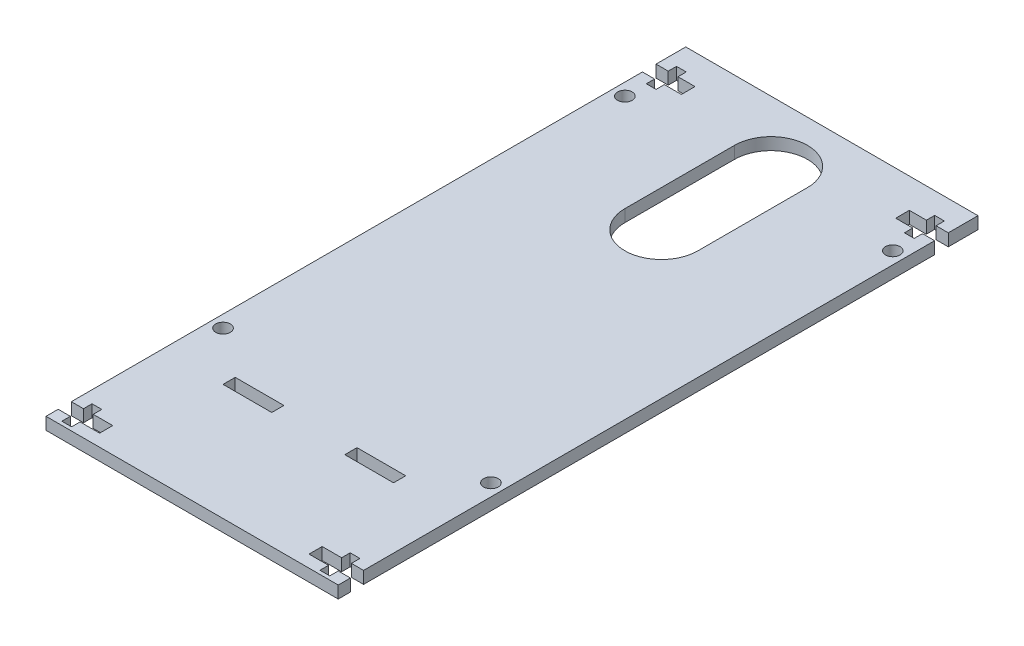
SolidWorks part; units mm, degrees
ref_plane "Front Plane" through (0, 0, 0) normal (0, 0, 1) x (1, 0, 0)
ref_plane "Top Plane" through (0, 0, 0) normal (0, 1, 0) x (1, 0, 0)
ref_plane "Right Plane" through (0, 0, 0) normal (1, 0, 0) x (0, 0, -1)
sketch "Sketch1" plane through (0, 0, 0) normal (0, 1, 0) x (1, 0, 0)
  line L0 (0, 0) -> (0, 170.1272) construction
  line L1 (-38.1, 4.8895) -> (-22.9165, 4.8895) construction
  line L2 (-38.1, 6.604) -> (-34.925, 6.604)
  line L3 (-34.925, 6.604) -> (-34.925, 8.8265)
  line L4 (-34.925, 8.8265) -> (-32.385, 8.8265)
  line L5 (0, 0) -> (-38.1, 0)
  line L6 (-38.1, 0) -> (-38.1, 3.175)
  line L7 (-38.1, 166.8145) -> (38.1, 166.8145)
  line L8 (-22.225, 33.4645) -> (-22.225, 30.2895)
  line L9 (-22.225, 30.2895) -> (-9.525, 30.2895)
  line L10 (-9.525, 30.2895) -> (-9.525, 33.4645)
  line L11 (-9.525, 33.4645) -> (-22.225, 33.4645)
  line L12 (-38.1, 159.0675) -> (-34.925, 159.0675)
  line L13 (-34.925, 159.0675) -> (-34.925, 161.2265)
  line L14 (-34.925, 161.2265) -> (-32.385, 161.2265)
  line L15 (-32.385, 161.2265) -> (-32.385, 159.0675)
  line L16 (-32.385, 159.0675) -> (-27.94, 159.0675)
  line L17 (-27.94, 159.0675) -> (-27.94, 155.5115)
  line L18 (-27.94, 157.2895) -> (-38.1, 157.2895) construction
  line L19 (-32.385, 155.5115) -> (-27.94, 155.5115)
  line L20 (-32.385, 153.3525) -> (-32.385, 155.5115)
  line L21 (-34.925, 153.3525) -> (-32.385, 153.3525)
  line L22 (-34.925, 155.5115) -> (-34.925, 153.3525)
  line L23 (-38.1, 155.5115) -> (-34.925, 155.5115)
  line L24 (-38.1, 159.0675) -> (-38.1, 166.8145)
  line L25 (27.94, 157.2895) -> (38.1, 157.2895) construction
  line L26 (38.1, 159.0675) -> (38.1, 166.8145)
  line L27 (38.1, 155.5115) -> (34.925, 155.5115)
  line L28 (34.925, 155.5115) -> (34.925, 153.3525)
  line L29 (34.925, 153.3525) -> (32.385, 153.3525)
  line L30 (32.385, 153.3525) -> (32.385, 155.5115)
  line L31 (32.385, 155.5115) -> (27.94, 155.5115)
  line L32 (27.94, 159.0675) -> (27.94, 155.5115)
  line L33 (32.385, 159.0675) -> (27.94, 159.0675)
  line L34 (32.385, 161.2265) -> (32.385, 159.0675)
  line L35 (34.925, 161.2265) -> (32.385, 161.2265)
  line L36 (34.925, 159.0675) -> (34.925, 161.2265)
  line L37 (38.1, 159.0675) -> (34.925, 159.0675)
  line L38 (9.525, 33.4645) -> (22.225, 33.4645)
  line L39 (9.525, 30.2895) -> (9.525, 33.4645)
  line L40 (22.225, 30.2895) -> (9.525, 30.2895)
  line L41 (22.225, 33.4645) -> (22.225, 30.2895)
  line L42 (38.1, 0) -> (38.1, 3.175)
  line L43 (0, 0) -> (38.1, 0)
  line L44 (-32.385, 8.8265) -> (-32.385, 6.604)
  line L45 (-32.385, 6.604) -> (-27.305, 6.604)
  line L46 (-27.305, 6.604) -> (-27.305, 3.175)
  line L47 (0, 150.9395) -> (0, 122.3645) construction
  line L48 (9.525, 150.9395) -> (9.525, 122.3645)
  line L49 (-9.525, 150.9395) -> (-9.525, 122.3645)
  line L50 (-32.385, 3.175) -> (-27.305, 3.175)
  line L51 (-32.385, 0.9525) -> (-32.385, 3.175)
  line L52 (-34.925, 0.9525) -> (-32.385, 0.9525)
  line L53 (-34.925, 3.175) -> (-34.925, 0.9525)
  line L54 (-38.1, 3.175) -> (-34.925, 3.175)
  line L55 (-38.1, 6.604) -> (-38.1, 155.5115)
  line L56 (-38.1, 6.604) -> (-34.925, 6.604)
  line L57 (-34.925, 6.604) -> (-34.925, 8.8265)
  line L58 (-34.925, 8.8265) -> (-32.385, 8.8265)
  line L59 (-32.385, 8.8265) -> (-32.385, 6.604)
  line L60 (-32.385, 6.604) -> (-27.305, 6.604)
  line L61 (-32.385, 3.175) -> (-27.305, 3.175)
  line L62 (-32.385, 0.9525) -> (-32.385, 3.175)
  line L63 (-34.925, 0.9525) -> (-32.385, 0.9525)
  line L64 (-34.925, 3.175) -> (-34.925, 0.9525)
  line L65 (-38.1, 3.175) -> (-34.925, 3.175)
  line L66 (38.1, 4.8895) -> (22.9165, 4.8895) construction
  line L67 (38.1, 3.175) -> (34.925, 3.175)
  line L68 (34.925, 3.175) -> (34.925, 0.9525)
  line L69 (34.925, 0.9525) -> (32.385, 0.9525)
  line L70 (32.385, 0.9525) -> (32.385, 3.175)
  line L71 (32.385, 3.175) -> (27.305, 3.175)
  line L72 (32.385, 6.604) -> (27.305, 6.604)
  line L73 (32.385, 8.8265) -> (32.385, 6.604)
  line L74 (34.925, 8.8265) -> (32.385, 8.8265)
  line L75 (34.925, 6.604) -> (34.925, 8.8265)
  line L76 (38.1, 6.604) -> (34.925, 6.604)
  line L77 (38.1, 3.175) -> (34.925, 3.175)
  line L78 (34.925, 3.175) -> (34.925, 0.9525)
  line L79 (34.925, 0.9525) -> (32.385, 0.9525)
  line L80 (32.385, 0.9525) -> (32.385, 3.175)
  line L81 (32.385, 3.175) -> (27.305, 3.175)
  line L82 (27.305, 6.604) -> (27.305, 3.175)
  line L83 (32.385, 6.604) -> (27.305, 6.604)
  line L84 (32.385, 8.8265) -> (32.385, 6.604)
  line L85 (34.925, 8.8265) -> (32.385, 8.8265)
  line L86 (34.925, 6.604) -> (34.925, 8.8265)
  line L87 (38.1, 6.604) -> (34.925, 6.604)
  line L88 (38.1, 6.604) -> (38.1, 155.5115)
  arc A0 (9.525, 150.9395) -> (-9.525, 150.9395) centre (0, 150.9395) ccw
  arc A1 (-9.525, 122.3645) -> (9.525, 122.3645) centre (0, 122.3645) ccw
  circle A2 centre (-34.925, 42.9895) radius 1.905
  circle A3 centre (-34.925, 147.7645) radius 1.905
  circle A4 centre (34.925, 42.9895) radius 1.905
  circle A5 centre (34.925, 147.7645) radius 1.905
  point P48 (0, 166.8145)
  point P55 (0, 136.652)
  point P70 (-27.305, 4.8895)
  point P89 (27.305, 4.8895)
  dimension "D19" = 3.81
  dimension "D24" = 3.175
  dimension "D1" = 133.35
  dimension "D2" = 3.175
  dimension "D3" = 12.7
  dimension "D4" = 9.525
  dimension "D5" = 38.1
  dimension "D6" = 152.4
  dimension "D7" = 3.175
  dimension "D8" = 2.54
  dimension "D9" = 1.778
  dimension "D10" = 10.16
  dimension "D11" = 9.525
  dimension "D12" = 3.937
  dimension "D13" = 1.7145
  dimension "D14" = 3.937
  dimension "D15" = 2.54
  dimension "D16" = 28.575
  dimension "D17" = 19.05
  dimension "D18" = 10.795
  dimension "D20" = 9.525
  dimension "D21" = 3.175
  dimension "D22" = 3.175
  dimension "D23" = 114.3
  dimension "D25" = 3.175
  dimension "D26" = 88.9
extrude "Boss-Extrude1" add sketch "Sketch1" along normal blind 3.175 contours L76 L88 L27 L28 L29 L30 L31 L32 L33 L34 L35 L36 L37 L26 L7 L24 L12 L13 L14 L15 L16 L17 L19 L20 L21 L22 L23 L55 L2 L3 L4 L44 L45 L46 L50 L51 L52 L53 L54 L6 L5 L43 L42 L67 L68 L69 L70 L71 L82 L72 L73
